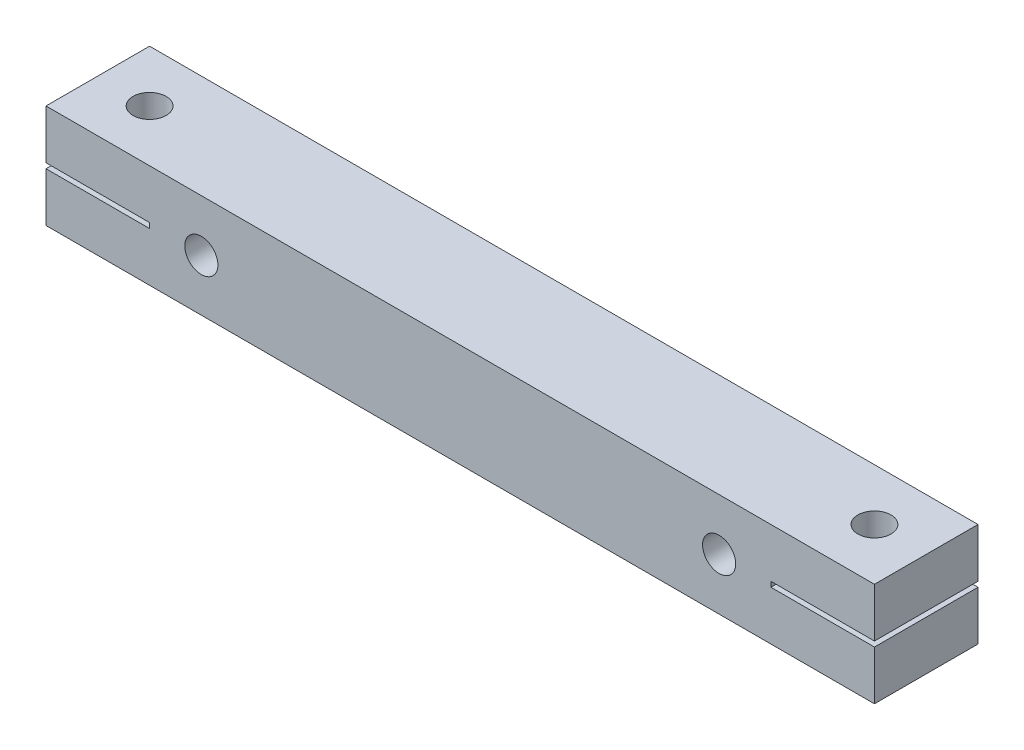
SolidWorks part; units mm, degrees
ref_plane "Front Plane" through (0, 0, 0) normal (0, 0, 1) x (1, 0, 0)
ref_plane "Top Plane" through (0, 0, 0) normal (0, 1, 0) x (1, 0, 0)
ref_plane "Right Plane" through (0, 0, 0) normal (1, 0, 0) x (0, 0, -1)
sketch "Sketch1" plane through (0, 0, 0) normal (0, 0, 1) x (1, 0, 0)
  line L0 (0, -5) -> (80, -5)
  line L1 (80, -5) -> (80, 5)
  line L2 (80, 5) -> (0, 5)
  line L3 (0, 5) -> (0, -5)
  point P6 (0, 0)
  dimension "D1" = 80
  dimension "D2" = 10
extrude "Boss-Extrude1" add sketch "Sketch1" along normal mid plane 10
sketch "Sketch2" plane through (0, 0, 5) normal (0, 0, 1) x (1, 0, 0)
  line L0 (0, 5) -> (0, -5) construction
  line L1 (0, 0.25) -> (10, 0.25)
  line L2 (0, 0.25) -> (0, -0.25)
  line L3 (0, -0.25) -> (10, -0.25)
  line L4 (10, 0.25) -> (10, -0.25)
  line L5 (80, -5) -> (80, 5) construction
  line L6 (80, 0.25) -> (70, 0.25)
  line L7 (80, 0.25) -> (80, -0.25)
  line L8 (80, -0.25) -> (70, -0.25)
  line L9 (70, 0.25) -> (70, -0.25)
  line L10 (80, 5) -> (0, 5) construction
  line L11 (0, 0.25) -> (0, -0.25)
  line L12 (80, 0.25) -> (80, -0.25)
  point P12 (10, 0)
  line M9 (0, 5) -> (0, -5)
  line M11 (80, -5) -> (80, 5)
  dimension "D1" = 5
  dimension "D2" = 0.5
  dimension "D3" = 10
extrude "Cut-Extrude1" cut sketch "Sketch2" against normal through all contours L4 L1 L3 M9 | L6 L9 L8 M11
sketch "Sketch3" plane through (0, 5, 0) normal (0, 1, 0) x (1, 0, 0)
  line L0 (0, 0) -> (80, 0) construction
  line L1 (0, -5) -> (0, 5) construction
  line L2 (80, -5) -> (80, 5) construction
  line L3 (40, -5) -> (40, 5) construction
  line L4 (80, -5) -> (0, -5) construction
  line L5 (80, 5) -> (0, 5) construction
  circle A0 centre (5, 0) radius 1.6
  circle A1 centre (75, 0) radius 1.6
  dimension "D1" = 5
  dimension "D2" = 3.2
extrude "Cut-Extrude2" cut sketch "Sketch3" against normal through all
sketch "Sketch4" plane through (0, 0, 0) normal (0, 0, 1) x (1, 0, 0)
  line L0 (0, 5) -> (0, 0) construction
  line L2 (0, 0) -> (80, 0) construction
  line L4 (80, 0) -> (100, 0) construction
  line L5 (0, 0) -> (-20, 0) construction
  line L6 (80, 0.25) -> (80, 5) construction
  circle A0 centre (-20, 0) radius 10 construction
  circle A1 centre (100, 0) radius 10 construction
  dimension "D1" = 20
  dimension "D2" = 20
sketch "Sketch5" plane through (0, 0, 5) normal (0, 0, 1) x (1, 0, 0)
  line L0 (0, 5) -> (0, 0.25) construction
  line L1 (0, 0) -> (15, 0) construction
  line L2 (15, 0) -> (65, 0) construction
  line L3 (80, 0.25) -> (80, 5) construction
  circle A0 centre (15, 0) radius 1.6
  circle A1 centre (65, 0) radius 1.6
  point P8 (0, 0)
  dimension "D1" = 3.2
  dimension "D2" = 15
  dimension "D3" = 15
extrude "Cut-Extrude3" cut sketch "Sketch5" against normal through all
equation "\"Leg_length\"= 80"
equation "\"D1@Sketch1\"=\"Leg_length\""
equation "\"Leg_width\"=10"
equation "\"D2@Sketch1\"=\"Leg_width\""
equation "\"D1@Sketch2\"=\"Leg_width\"/2"
equation "\"Leaf_Spring_Thickness\"= 0.5"
equation "\"D2@Sketch2\"=\"Leaf_Spring_Thickness\""
equation "\"Leaf_Spring_Slot_Depth\"=10"
equation "\"D3@Sketch2\"=\"Leaf_Spring_Slot_Depth\""
equation "\"D1@Sketch3\"=\"Leaf_Spring_Slot_Depth\"/2"
equation "\"Leaf_Spring_Radii\"=20"
equation "\"D2@Sketch4\"=\"Leaf_Spring_Radii\""
